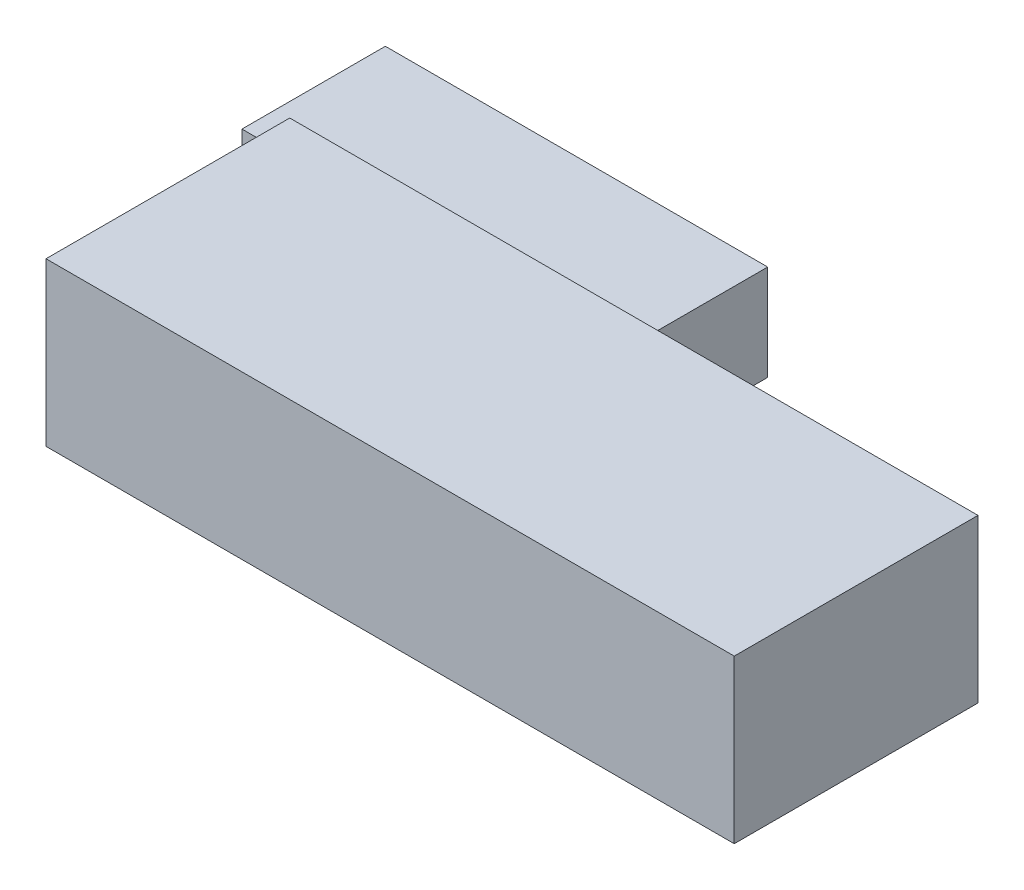
SolidWorks part; units mm, degrees
ref_plane "Front Plane" through (0, 0, 0) normal (0, 0, 1) x (1, 0, 0)
ref_plane "Top Plane" through (0, 0, 0) normal (0, 1, 0) x (1, 0, 0)
ref_plane "Right Plane" through (0, 0, 0) normal (1, 0, 0) x (0, 0, -1)
sketch "Sketch1" plane through (0, 0, 0) normal (0, 1, 0) x (1, 0, 0)
  line L1 (-72, -25.5) -> (72, -25.5)
  line L2 (-72, -25.5) -> (-72, 25.5)
  line L3 (-72, 25.5) -> (72, 25.5)
  line L4 (72, -25.5) -> (72, 25.5)
  line L5 (-72, -25.5) -> (72, 25.5) construction
  line L6 (-72, 25.5) -> (72, -25.5) construction
  point P0 (0, 0)
  dimension "D1" = 144
  dimension "D2" = 51
extrude "Boss-Extrude1" add sketch "Sketch1" along normal blind 34
sketch "Sketch2" plane through (0, 0, -25.5) normal (0, 0, -1) x (-1, 0, 0)
  line L0 (-72, 17) -> (72, 17) construction
  line L1 (-72, 34) -> (-72, 0) construction
  line L2 (72, 34) -> (72, 0) construction
  line L4 (2, 7) -> (82, 7)
  line L5 (2, 7) -> (2, 27)
  line L6 (2, 27) -> (82, 27)
  line L7 (82, 7) -> (82, 27)
  line L8 (2, 7) -> (82, 27) construction
  line L9 (2, 27) -> (82, 7) construction
  point P6 (42, 17)
  dimension "D1" = 20
  dimension "D2" = 80
  dimension "D3" = 10
extrude "Boss-Extrude2" add sketch "Sketch2" along normal blind 30
